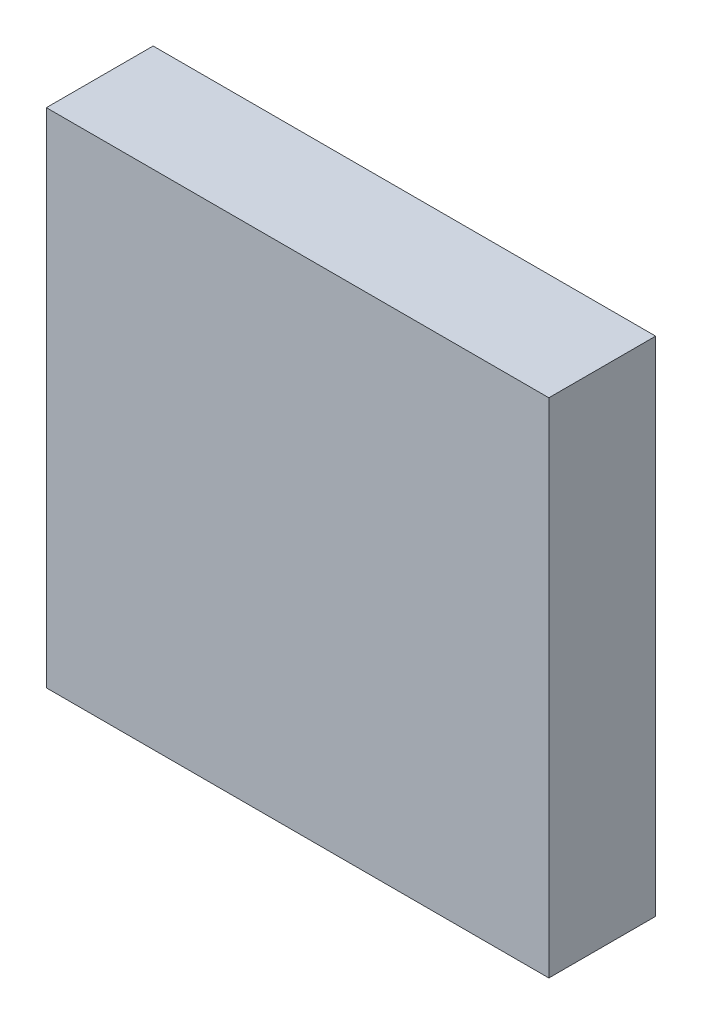
SolidWorks part; units mm, degrees
ref_plane "前视基准面" through (0, 0, 0) normal (0, 0, 1) x (1, 0, 0)
ref_plane "上视基准面" through (0, 0, 0) normal (0, 1, 0) x (1, 0, 0)
ref_plane "右视基准面" through (0, 0, 0) normal (1, 0, 0) x (0, 0, -1)
sketch "草图1" plane through (0, 0, 0) normal (0, 0, 1) x (1, 0, 0)
  line L0 (-4, 4) -> (4, 4)
  line L1 (4, 4) -> (4, -4)
  line L2 (4, -4) -> (-4, -4)
  line L3 (-4, -4) -> (-4, 3.2)
  line L4 (-4, 3.2) -> (-4, 4)
extrude "Component_Outline" add sketch "草图1" along normal blind 1.7 separate body
sketch3d "3D草图1"
  line L0 (0, 0, 0) -> (1, 0, 0)
  line L1 (0, 0, 0) -> (0, 1, 0)
  line L2 (0, 0, 0) -> (0, 0, 1)
  point P0 (0, 0, 0)
